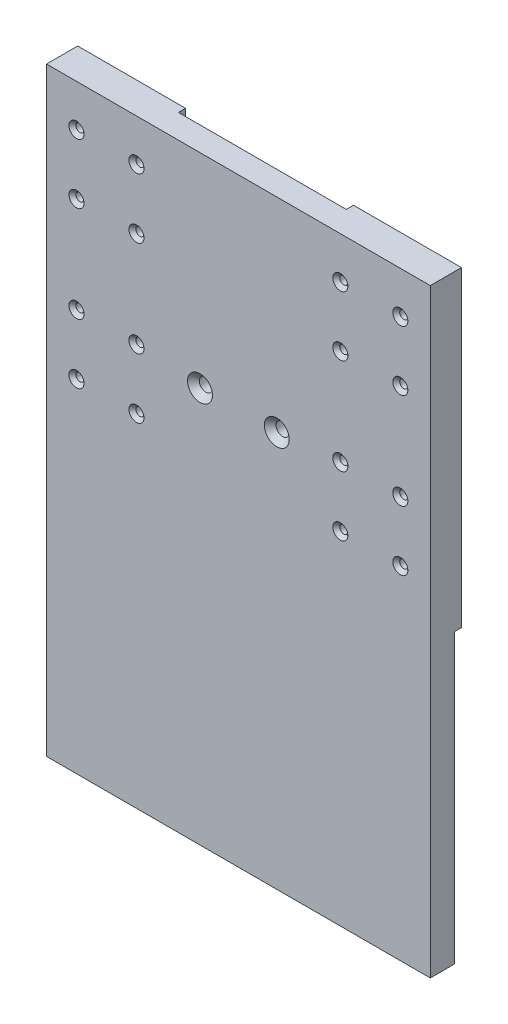
SolidWorks part; units mm, degrees
material "3.1355 (EN-AW 2024)"
ref_plane "Front" through (0, 0, 0) normal (0, 0, 1) x (1, 0, 0)
ref_plane "Top" through (0, 0, 0) normal (0, 1, 0) x (1, 0, 0)
ref_plane "Right" through (0, 0, 0) normal (1, 0, 0) x (0, 0, -1)
sketch "Эскиз1" plane through (0, 0, 0) normal (0, 0, 1) x (1, 0, 0)
  line L1 (-80, 125) -> (80, 125)
  line L2 (-80, 125) -> (-80, -125)
  line L3 (-80, -125) -> (80, -125)
  line L4 (80, 125) -> (80, -125)
  line L5 (-80, 125) -> (80, -125) construction
  line L6 (-80, -125) -> (80, 125) construction
  point P0 (0, 0)
  dimension "D1" = 160
  dimension "D2" = 250
extrude "База" add sketch "Эскиз1" along normal blind 10
sketch "Эскиз6" plane through (0, 0, 0) normal (0, 0, -1) x (-1, 0, 0)
  line L1 (-80, 125) -> (-35, 125)
  line L2 (-80, 125) -> (-80, -5)
  line L3 (-80, -5) -> (-35, -5)
  line L4 (-35, 125) -> (-35, -5)
  line L5 (80, 125) -> (35, 125)
  line L6 (80, 125) -> (80, -5)
  line L7 (80, -5) -> (35, -5)
  line L8 (35, 125) -> (35, -5)
  dimension "D1" = 45
  dimension "D2" = 130
extrude "Вынос плиты" add sketch "Эскиз6" along normal blind 3
hole_wizard "Каретки-M3" positions "Эскиз2" profile "Эскиз3" countersink size "M3" standard "ISO" end condition through all
sketch "Эскиз2" plane through (0, 0, 10) normal (0, 0, 1) x (1, 0, 0)
  line L0 (-42.5, 82.5) -> (-42.5, 62.5) construction
  line L1 (-42.5, 62.5) -> (-42.5, 42.5) construction
  line L4 (42.5, 82.5) -> (42.5, 62.5) construction
  line L5 (42.5, 62.5) -> (42.5, 42.5) construction
  line L12 (-67.5, 82.5) -> (-42.5, 82.5) construction
  line L15 (42.5, 82.5) -> (67.5, 82.5) construction
  line L18 (-42.5, 82.5) -> (-42.5, 107.5) construction
  line L21 (42.5, 82.5) -> (42.5, 107.5) construction
  line L24 (-42.5, 42.5) -> (-42.5, 17.5) construction
  line L27 (42.5, 42.5) -> (42.5, 17.5) construction
  line L28 (-55, 62.5) -> (0, 62.5) construction
  line L29 (0, 62.5) -> (55, 62.5) construction
  point P0 (-67.5, 107.5)
  point P2 (-42.5, 107.5)
  point P4 (-42.5, 82.5)
  point P6 (-67.5, 82.5)
  point P8 (42.5, 107.5)
  point P10 (67.5, 107.5)
  point P12 (67.5, 82.5)
  point P14 (42.5, 82.5)
  point P16 (-67.5, 42.5)
  point P18 (-42.5, 42.5)
  point P20 (-42.5, 17.5)
  point P22 (-67.5, 17.5)
  point P24 (42.5, 42.5)
  point P26 (67.5, 42.5)
  point P28 (67.5, 17.5)
  point P30 (42.5, 17.5)
  point P89 (-55, 82.5)
  point P90 (55, 82.5)
  dimension "D1" = 25
  dimension "D2" = 25
  dimension "D3" = 90
  dimension "D4" = 62.5
  dimension "D5" = 110
sketch "Эскиз3" plane through (-67.5, 107.5, 10) normal (1, 0, 0) x (0, -1, 0)
  line L0 (0, 0) -> (0, 13)
  line L1 (0, 13) -> (1.7, 13)
  line L2 (1.7, 13) -> (1.7, 1.45)
  line L3 (1.7, 1.45) -> (3.15, 0)
  line L5 (3.15, 0) -> (0, 0)
  line L6 (-1.7, 1.45) -> (-3.15, 0) construction
  line L11 (0, -6.35) -> (0, 107.95) construction
  dimension "Диаметр сквозного отверстия" = 3.4
  dimension "Глубина сквозного отверстия" = 13
  dimension "Диаметр передней зенковки" = 6.3
  dimension "Угол передней зенковки" = 90
hole_wizard "Гайка ШВП - M5" positions "Эскиз4" profile "Эскиз5" countersink size "M5" standard "ISO" end condition through all
sketch "Эскиз4" plane through (0, 0, 10) normal (0, 0, 1) x (1, 0, 0)
  line L0 (-16, 40) -> (0, 40) construction
  line L1 (0, 40) -> (16, 40) construction
  line L4 (-42.5, 82.5) -> (-42.5, 62.5) construction
  line L5 (-42.5, 62.5) -> (-42.5, 42.5) construction
  point P0 (-16, 40)
  point P2 (16, 40)
  dimension "D1" = 32
  dimension "D2" = 40
sketch "Эскиз5" plane through (-16, 40, 10) normal (1, 0, 0) x (0, -1, 0)
  line L0 (0, 0) -> (0, 13)
  line L1 (0, 13) -> (2.75, 13)
  line L2 (2.75, 13) -> (2.75, 2.45)
  line L3 (2.75, 2.45) -> (5.2, 0)
  line L5 (5.2, 0) -> (0, 0)
  line L6 (-2.75, 2.45) -> (-5.2, 0) construction
  line L11 (0, -6.35) -> (0, 107.95) construction
  dimension "Диаметр сквозного отверстия" = 5.5
  dimension "Глубина сквозного отверстия" = 13
  dimension "Диаметр передней зенковки" = 10.4
  dimension "Угол передней зенковки" = 90
